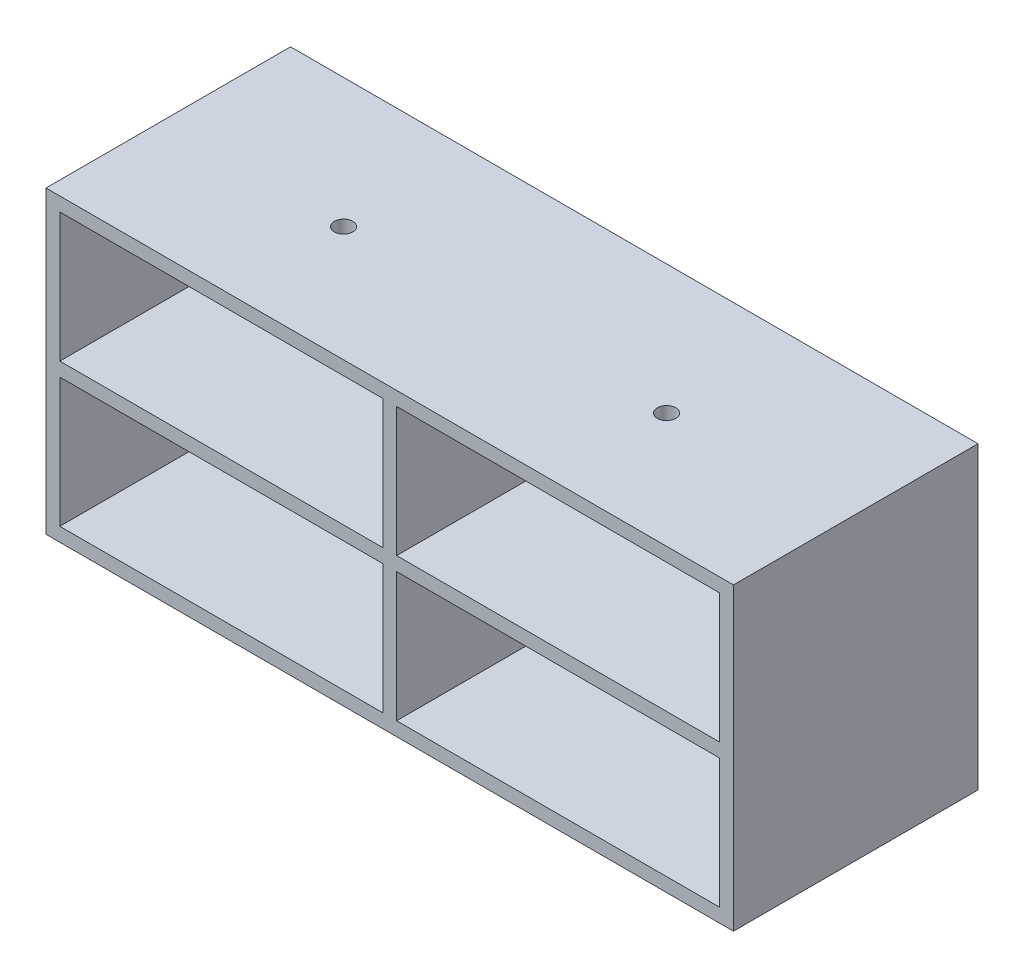
SolidWorks part; units mm, degrees
ref_plane "Front Plane" through (0, 0, 0) normal (0, 0, 1) x (1, 0, 0)
ref_plane "Top Plane" through (0, 0, 0) normal (0, 1, 0) x (1, 0, 0)
ref_plane "Right Plane" through (0, 0, 0) normal (1, 0, 0) x (0, 0, -1)
sketch "Sketch1" plane through (0, 0, 0) normal (0, 0, 1) x (1, 0, 0)
  line L1 (0, 0) -> (149, 0)
  line L2 (0, 0) -> (0, -65)
  line L3 (0, -65) -> (149, -65)
  line L4 (149, 0) -> (149, -65)
  dimension "D1" = 149
  dimension "D2" = 65
extrude "Boss-Extrude1" add sketch "Sketch1" along normal blind 3
sketch "Sketch2" plane through (0, 0, 3) normal (0, 0, 1) x (1, 0, 0)
  line L0 (146, -3) -> (3, -3)
  line L1 (3, -3) -> (3, -62)
  line L2 (3, -62) -> (146, -62)
  line L3 (146, -62) -> (146, -3)
  line L4 (0, 0) -> (0, -65)
  line L5 (0, -65) -> (149, -65)
  line L6 (149, -65) -> (149, 0)
  line L7 (149, 0) -> (0, 0)
  line L8 (0, 0) -> (0, -65)
  line L9 (0, -65) -> (149, -65)
  line L10 (149, -65) -> (149, 0)
  line L11 (149, 0) -> (0, 0)
  dimension "D1" = 0
  dimension "D2" = 3
extrude "Boss-Extrude2" add sketch "Sketch2" along normal blind 50
sketch "Sketch4" plane through (0, 0, 3) normal (0, 0, 1) x (1, 0, 0)
  line L0 (146, -3) -> (3, -3) construction
  line L1 (73, -3) -> (73, -31)
  line L2 (73, -31) -> (3, -31)
  line L3 (3, -3) -> (3, -62) construction
  line L4 (3, -31) -> (3, -34)
  line L5 (3, -34) -> (73, -34)
  line L6 (73, -34) -> (73, -62)
  line L7 (3, -62) -> (146, -62) construction
  line L8 (73, -62) -> (76, -62)
  line L9 (3, -62) -> (146, -62) construction
  line L10 (76, -62) -> (76, -34)
  line L11 (76, -34) -> (146, -34)
  line L12 (146, -62) -> (146, -3) construction
  line L13 (146, -34) -> (146, -31)
  line L14 (146, -62) -> (146, -3) construction
  line L15 (146, -31) -> (76, -31)
  line L16 (76, -31) -> (76, -3)
  line L17 (146, -3) -> (3, -3) construction
  line L18 (76, -3) -> (73, -3)
  line L19 (3, -3) -> (3, -62) construction
  dimension "D1" = 3
  dimension "D2" = 3
  dimension "D3" = 3
  dimension "D4" = 3
  dimension "D5" = 70
  dimension "D6" = 70
  dimension "D7" = 28
extrude "Boss-Extrude3" add sketch "Sketch4" along normal up to surface (50 mm away) up to face at (74.5, -32.5, 53)
sketch "Sketch5" plane through (0, 0, 0) normal (0, 1, 0) x (1, 0, 0)
  line L0 (74.5, 0) -> (74.5, -53) construction
  line L1 (149, 0) -> (0, 0) construction
  line L2 (149, -53) -> (0, -53) construction
  circle A0 centre (39.5, -28) radius 2
  circle A1 centre (109.5, -28) radius 2
  dimension "D1" = 4
  dimension "D2" = 4
  dimension "D3" = 25
  dimension "D4" = 35
extrude "Cut-Extrude1" cut sketch "Sketch5" against normal up to surface (3 mm away) up to face at (111, -3, 28)
